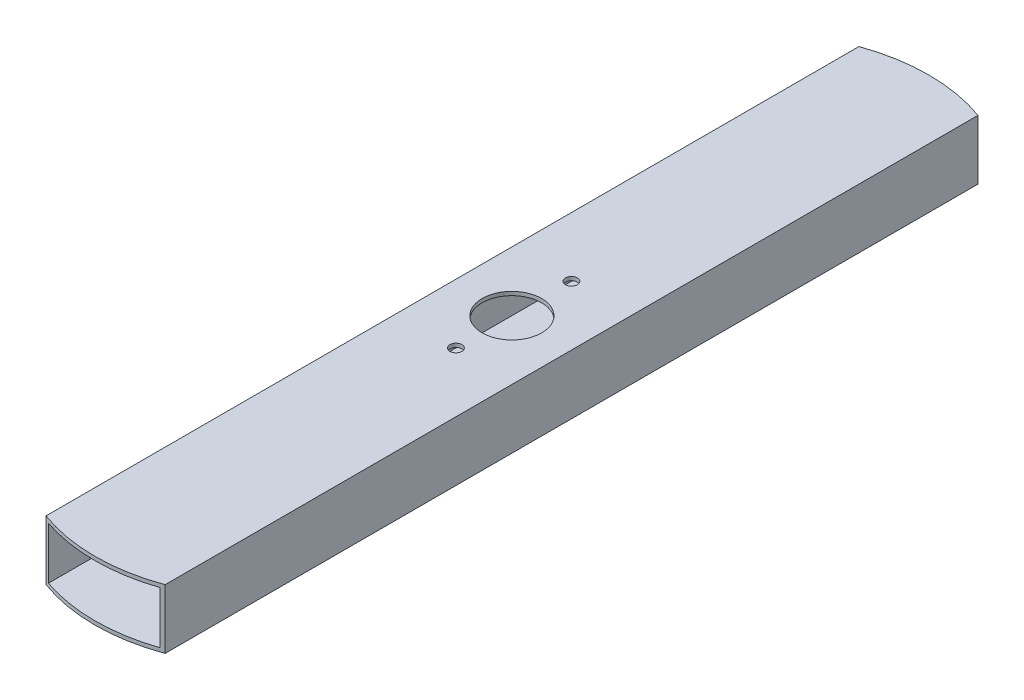
SolidWorks part; units mm, degrees
ref_plane "Front Plane" through (0, 0, 0) normal (0, 0, 1) x (1, 0, 0)
ref_plane "Top Plane" through (0, 0, 0) normal (0, 1, 0) x (1, 0, 0)
ref_plane "Right Plane" through (0, 0, 0) normal (1, 0, 0) x (0, 0, -1)
sketch "Sketch1" plane through (0, 0, 0) normal (0, 0, 1) x (1, 0, 0)
  line L1 (23.8125, -11.1125) -> (-23.8125, -11.1125)
  line L2 (23.8125, -11.1125) -> (23.8125, 11.1125)
  line L3 (23.8125, 11.1125) -> (-23.8125, 11.1125)
  line L4 (-23.8125, -11.1125) -> (-23.8125, 11.1125)
  line L5 (23.8125, -11.1125) -> (-23.8125, 11.1125) construction
  line L6 (23.8125, 11.1125) -> (-23.8125, -11.1125) construction
  line L7 (25.4, -12.7) -> (-25.4, -12.7)
  line L8 (25.4, -12.7) -> (25.4, 12.7)
  line L9 (25.4, 12.7) -> (-25.4, 12.7)
  line L10 (-25.4, -12.7) -> (-25.4, 12.7)
  line L11 (25.4, -12.7) -> (-25.4, 12.7) construction
  line L12 (25.4, 12.7) -> (-25.4, -12.7) construction
  point P0 (0, 0)
  point P6 (0, 0)
  dimension "D1" = 50.8
  dimension "D2" = 25.4
  dimension "D3" = 1.5875
  dimension "D4" = 1.5875
extrude "Boss-Extrude1" add sketch "Sketch1" along normal blind 355.6
sketch "Sketch2" plane through (0, 12.7, 0) normal (0, 1, 0) x (1, 0, 0)
  line L0 (0, 0) -> (0, -355.6) construction
  line L1 (25.4, 0) -> (-25.4, 0) construction
  line L2 (25.4, -355.6) -> (-25.4, -355.6) construction
  circle A0 centre (0, -177.8) radius 12.7
  circle A1 centre (0, -152.4) radius 2.54
  circle A2 centre (0, -201.676) radius 2.54
  dimension "D1" = 25.4
  dimension "D2" = 5.08
  dimension "D3" = 23.876
  dimension "D4" = 25.4
extrude "Cut-Extrude4" cut sketch "Sketch2" against normal blind 32.766
sketch "Sketch3" plane through (0, -12.7, 0) normal (0, -1, 0) x (1, 0, 0)
  line L1 (-25.4, 0) -> (25.4, 0)
  line L2 (-25.4, 0) -> (-25.4, 355.6)
  line L3 (-25.4, 355.6) -> (25.4, 355.6)
  line L4 (25.4, 0) -> (25.4, 355.6)
  circle A0 centre (0, 281.94) radius 73.66
  circle A1 centre (0, 74.93) radius 74.93
  line M9 (-25.4, 0) -> (25.4, 0)
  line M10 (25.4, 0) -> (25.4, 355.6)
  line M11 (25.4, 355.6) -> (-25.4, 355.6)
  line M12 (-25.4, 355.6) -> (-25.4, 0)
  dimension "D1" = 73.66
  dimension "D2" = 74.93
extrude "Cut-Extrude5" cut sketch "Sketch3" against normal up to next contours A0 M10 M11 | A0 L3 M12 | A1 L1 M10 | A1 M12 M9
